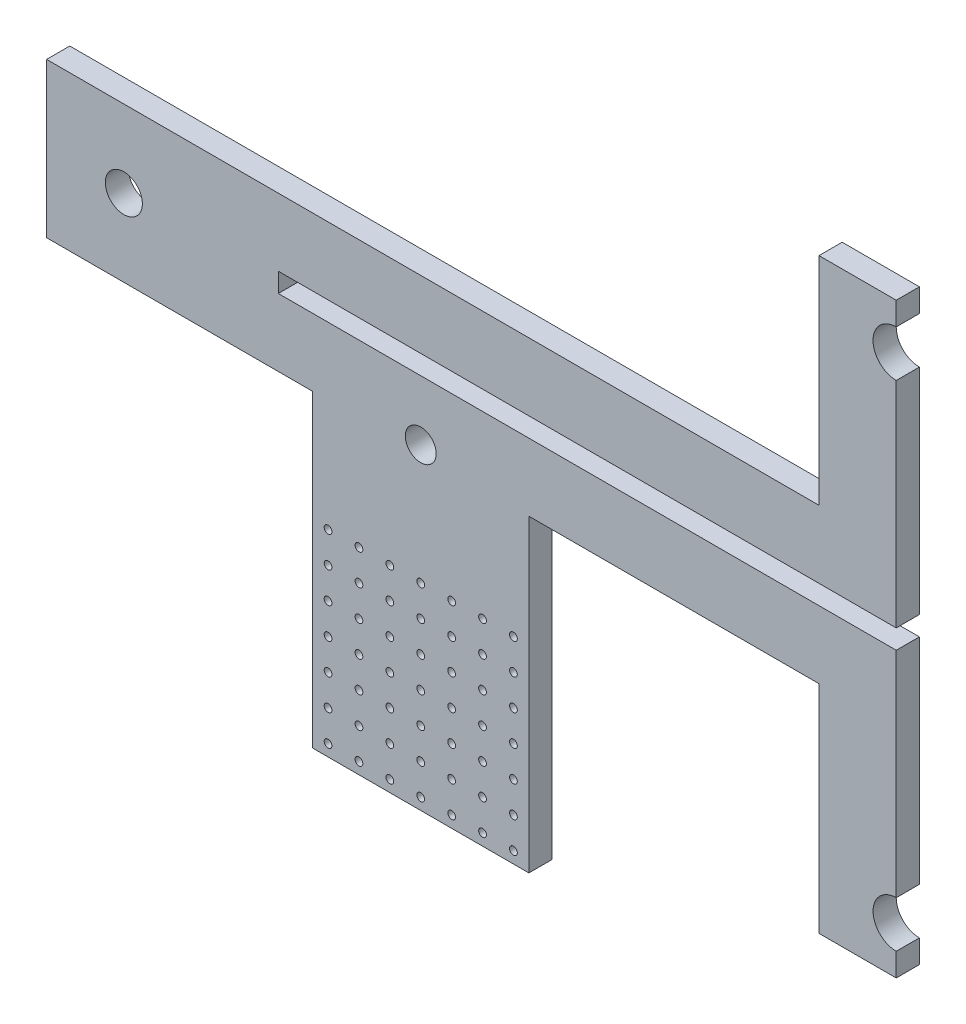
SolidWorks part; units mm, degrees
ref_plane "Front Plane" through (0, 0, 0) normal (0, 0, 1) x (1, 0, 0)
ref_plane "Top Plane" through (0, 0, 0) normal (0, 1, 0) x (1, 0, 0)
ref_plane "Right Plane" through (0, 0, 0) normal (1, 0, 0) x (0, 0, -1)
sketch "Sketch1" plane through (0, 0, 0) normal (0, 0, 1) x (1, 0, 0)
  line L4 (50, -5) -> (45, -5)
  line L5 (50, 5) -> (45, 5)
  line L10 (45, -5) -> (45, -19)
  line L11 (45, -19) -> (50, -19)
  line L13 (50, -5) -> (45, -5)
  line L14 (50, -19) -> (50, -5)
  line L15 (45, 19) -> (50, 19)
  line L16 (45, 5) -> (45, 19)
  line L17 (50, 5) -> (45, 5)
  line L18 (50, 19) -> (50, 5)
  line L19 (50, -5) -> (50, 5)
  line L20 (50, 5) -> (-5, 5)
  line L21 (-5, 5) -> (-5, -5)
  line L22 (50, -5) -> (-5, -5)
  line L23 (-5, 0) -> (0, 0)
  line L25 (19.22, -1) -> (19.22, -5)
  line L26 (50, -19) -> (47.5, -19)
  line L38 (19.22, -25) -> (19.22, -24)
  line L39 (19.22, -5) -> (26.22, -5)
  line L40 (26.22, -5) -> (26.22, -25)
  line L41 (26.22, -25) -> (12.22, -25)
  line L42 (12.22, -25) -> (12.22, -5)
  line L43 (12.22, -5) -> (19.22, -5)
  arc A1 (50, 14.5) -> (50, 17.5) centre (50, 16) cw
  arc A2 (50, -14.5) -> (50, -17.5) centre (50, -16) ccw
  circle A3 centre (0, 0) radius 1.2
  circle A4 centre (19.22, -6) radius 1
extrude "Boss-Extrude1" add sketch "Sketch1" along normal blind 1.5
sketch "Sketch2" plane through (0, 0, 1.5) normal (0, 0, 1) x (1, 0, 0)
  line L0 (19.22, -25) -> (19.22, -24.25)
  line L1 (26.22, -25) -> (12.22, -25) construction
  circle A0 centre (19.22, -24.25) radius 0.25
  circle A1 centre (21.22, -24.25) radius 0.25
  circle A2 centre (23.22, -24.25) radius 0.25
  circle A3 centre (25.22, -24.25) radius 0.25
  circle A4 centre (17.22, -24.25) radius 0.25
  circle A5 centre (15.22, -24.25) radius 0.25
  circle A6 centre (13.22, -24.25) radius 0.25
  circle A7 centre (13.22, -22.25) radius 0.25
  circle A8 centre (15.22, -22.25) radius 0.25
  circle A9 centre (17.22, -22.25) radius 0.25
  circle A10 centre (19.22, -22.25) radius 0.25
  circle A11 centre (21.22, -22.25) radius 0.25
  circle A12 centre (23.22, -22.25) radius 0.25
  circle A13 centre (25.22, -22.25) radius 0.25
  circle A14 centre (13.22, -20.25) radius 0.25
  circle A15 centre (15.22, -20.25) radius 0.25
  circle A16 centre (17.22, -20.25) radius 0.25
  circle A17 centre (19.22, -20.25) radius 0.25
  circle A18 centre (21.22, -20.25) radius 0.25
  circle A19 centre (23.22, -20.25) radius 0.25
  circle A20 centre (25.22, -20.25) radius 0.25
  circle A21 centre (13.22, -18.25) radius 0.25
  circle A22 centre (15.22, -18.25) radius 0.25
  circle A23 centre (17.22, -18.25) radius 0.25
  circle A24 centre (19.22, -18.25) radius 0.25
  circle A25 centre (21.22, -18.25) radius 0.25
  circle A26 centre (23.22, -18.25) radius 0.25
  circle A27 centre (25.22, -18.25) radius 0.25
  circle A28 centre (13.22, -16.25) radius 0.25
  circle A29 centre (15.22, -16.25) radius 0.25
  circle A30 centre (17.22, -16.25) radius 0.25
  circle A31 centre (19.22, -16.25) radius 0.25
  circle A32 centre (21.22, -16.25) radius 0.25
  circle A33 centre (23.22, -16.25) radius 0.25
  circle A34 centre (25.22, -16.25) radius 0.25
  circle A35 centre (13.22, -14.25) radius 0.25
  circle A36 centre (15.22, -14.25) radius 0.25
  circle A37 centre (17.22, -14.25) radius 0.25
  circle A38 centre (19.22, -14.25) radius 0.25
  circle A39 centre (21.22, -14.25) radius 0.25
  circle A40 centre (23.22, -14.25) radius 0.25
  circle A41 centre (25.22, -14.25) radius 0.25
  circle A42 centre (13.22, -12.25) radius 0.25
  circle A43 centre (15.22, -12.25) radius 0.25
  circle A44 centre (17.22, -12.25) radius 0.25
  circle A45 centre (19.22, -12.25) radius 0.25
  circle A46 centre (21.22, -12.25) radius 0.25
  circle A47 centre (23.22, -12.25) radius 0.25
  circle A48 centre (25.22, -12.25) radius 0.25
  dimension "D1" = 4
  dimension "D2" = 4
  dimension "D3" = 3
sketch "Sketch3" plane through (50, 0, 0) normal (1, 0, 0) x (0, 0, -1)
  line L0 (0, 0) -> (0, -0.625)
  line L1 (0, -14.5) -> (0, 14.5) construction
  line L2 (0, 0) -> (0, 0.625)
  line L3 (0, 0.625) -> (-1.5, 0.625)
  line L4 (-1.5, -14.5) -> (-1.5, 14.5) construction
  line L5 (-1.5, 0.625) -> (-1.5, -0.625)
  line L6 (-1.5, -0.625) -> (0, -0.625)
extrude "Cut-Extrude2" cut sketch "Sketch3" against normal blind 40
extrude "Cut-Extrude4" cut sketch "Sketch2" against normal blind 1.5 contours A1 | A17 | A18 | A19 | A2 | A20 | A27 | A26 | A33 | A5 | A11 | A0 | A10 | A24 | A31 | A38 | A45 | A46 | A39 | A32 | A25 | A12 | A3 | A13 | A34 | A47 | A48 | A40 | A41 | A4 | A9 | A16 | A23 | A30 | A37 | A44 | A8 | A15 | A22 | A29 | A36 | A43 | A42 | A35 | A28 | A21 | A14 | A7 | A6
sketch "Sketch4" plane through (0, 0, 1.5) normal (0, 0, 1) x (1, 0, 0)
  line L0 (0, 0) -> (19.22, 0)
  line L1 (19.22, 0) -> (19.22, -4.5)
  circle A0 centre (19.22, -4.5) radius 1
extrude "Cut-Extrude5" cut sketch "Sketch4" against normal blind 1.5
